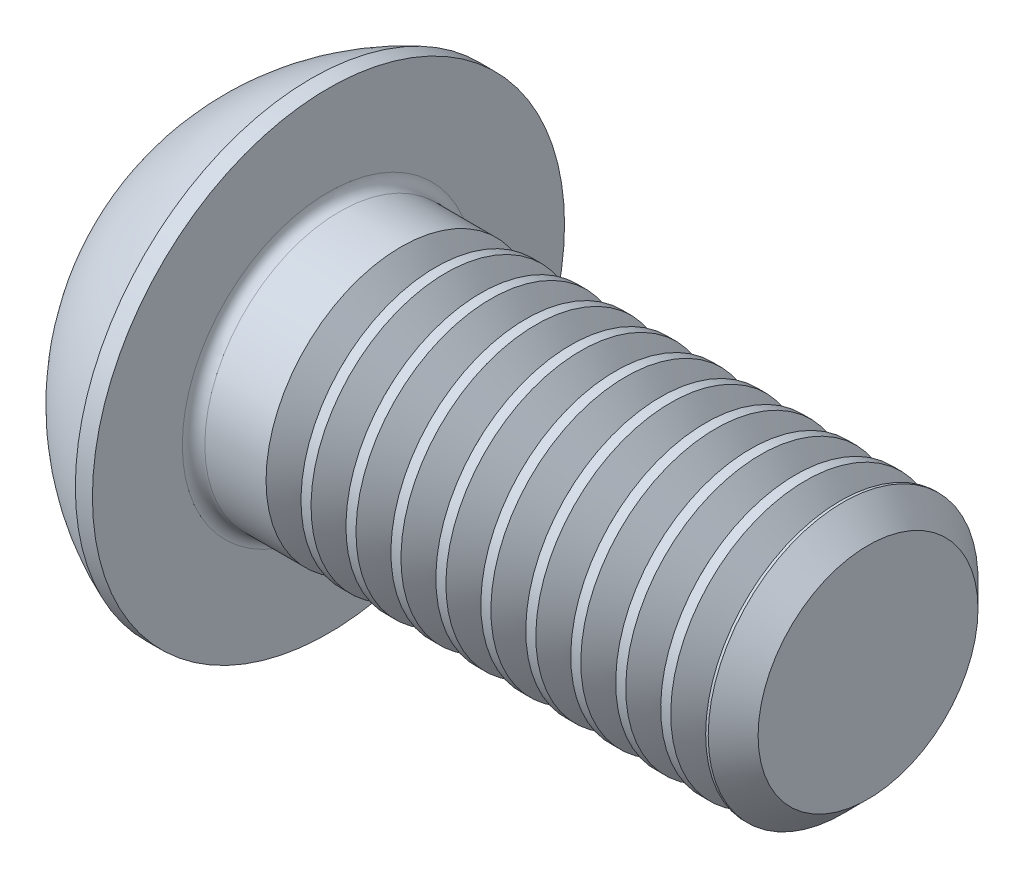
SolidWorks part; units mm, degrees
ref_plane "Plane1" through (0, 0, 0) normal (0, 0, 1) x (1, 0, 0)
ref_plane "Plane2" through (0, 0, 0) normal (0, 1, 0) x (1, 0, 0)
ref_plane "Plane3" through (0, 0, 0) normal (1, 0, 0) x (0, 0, -1)
other "Configuration Table"
sketch "BodySke" plane through (0, 0, 0) normal (0, 0, 1) x (1, 0, 0)
  line L0 (15.3, 0) -> (15.3, 2.4455)
  line L1 (14.7455, 3) -> (3.3, 3)
  line L2 (3.3, 3) -> (3.3, 5.25)
  line L3 (3.3, 5.25) -> (2.92, 5.25)
  line L4 (0, 0) -> (101.6, 0) construction
  line L5 (3.3, -5.25) -> (2.92, -5.25) construction
  line L6 (55.6768, -3) -> (3.3, -3) construction
  line L7 (15.3, 0) -> (0, 0)
  line L8 (0, 2.625) -> (0, -2.625) construction
  line L9 (0, 0) -> (0, 2.625)
  line L10 (15.3, 2.4455) -> (14.7455, 3)
  line L11 (15.3, -2.4455) -> (14.7455, -3) construction
  line L12 (4.3, 9.525) -> (4.3, -3) construction
  line L13 (3.3, 9.525) -> (3.3, -3) construction
  arc A1 (0, 2.625) -> (2.92, 5.25) centre (4.9997, 0) cw
  dimension "Diameter" = 6
  dimension "Length" = 12
  dimension "Head_dia" = 10.5
  dimension "D1" = 5.25
  dimension "Head_ht" = 3.3
  dimension "Head_side_ht" = 0.38
  dimension "Minor_dia" = 4.891
  dimension "Body_ch_ang" = 45
  dimension "Advance" = 1
  dimension "Thread_nom" = 12
revolve "BaseBody" add sketch "BodySke" angle 360 about L4
cosmetic thread "ThreadCosmetic" [suppressed] parameters "Thread_length"=10, "Thread_minor"=4.891
fillet "Fillet1" radius 0.25 1 edges at (3.3, 0, 3)
sketch "Sketch2" plane through (0, 0, 0) normal (0, 0, 1) x (1, 0, 0)
  line L0 (0, 2) -> (2.08, 2)
  line L1 (2.08, 2) -> (3.2347, 0)
  line L3 (3.2347, 0) -> (0, 0)
  line L4 (0, 0) -> (0, 2)
  line L5 (0, -2) -> (2.08, -2) construction
  line L6 (0, 0) -> (47.625, 0) construction
  dimension "D2" = 60
  dimension "PreBroach_depth" = 2.08
  dimension "PreBroach_dia" = 4
revolve "PreBroach" cut sketch "Sketch2" angle 360 about L6
sketch "Sketch3" plane through (0, 0, 0) normal (1, 0, 0) x (0, 0, -1)
  line L0 (-2, -1.1547) -> (-2, 1.1547)
  line L1 (-2, 1.1547) -> (0, 2.3094)
  line L2 (0, 2.3094) -> (2, 1.1547)
  line L3 (2, 1.1547) -> (2, -1.1547)
  line L4 (2, -1.1547) -> (0, -2.3094)
  line L5 (0, -2.3094) -> (-2, -1.1547)
  dimension "Hex_size" = 4
  dimension "D3" = 4
  dimension "D1" = 2
  dimension "D2" = 2
extrude "Hex" cut sketch "Sketch3" along normal blind 2.08
sketch "ThdSchSke" plane through (0, 0, 0) normal (0, 0, 1) x (1, 0, 0)
  line L0 (5.3, -2.4455) -> (4.9117, -3)
  line L1 (5.3, -2.4455) -> (5.6883, -3)
  line L2 (5.6883, -3) -> (5.6883, -3.75)
  line L3 (-3.175, 0) -> (5.1513, 0) construction
  line L5 (5.6883, -3.75) -> (4.9117, -3.75)
  line L6 (4.9117, -3.75) -> (4.9117, -3)
  dimension "Diameter" = 6
  dimension "Thread_minor" = 4.891
  dimension "SideAngle" = 55
  dimension "VeeAngle" = 70
  dimension "Overcut" = 7.5
  dimension "Start" = 5.3
revolve "ThreadSchematic" cut sketch "ThdSchSke" angle 360 about L3
pattern_linear "ThdSchPat" count 10 spacing 1 along (1, 0, 0) of "ThreadSchematic"
equation "\"D1@BodySke\" = \"Head_dia@BodySke\" * .5"
equation "\"Thread_minor@ThreadCosmetic\" = \"Minor_dia@BodySke\""
equation "\"D1@Sketch3\" = \"Hex_size@Sketch3\" / 2"
equation "\"D2@Sketch3\" = \"D1@Sketch3\""
equation "\"D3@Sketch3\" = \"Hex_size@Sketch3\""
equation "\"Thread_length@ThreadCosmetic\" = ((sgn( (\"Length@BodySke\" - \"Advance@BodySke\" * 2.0) - \"Thread_nom@BodySke\" )-1)*( (\"Length@BodySke\" - \"Advance@BodySke\" * 2.0) - \"Thread_nom@BodySke\" ))/-2+ \"Thread_nom@BodySke\""
equation "\"Thread_minor@ThdSchSke\" = \"Minor_dia@BodySke\""
equation "\"Diameter@ThdSchSke\" = \"Diameter@BodySke\""
equation "\"Overcut@ThdSchSke\" = \"Diameter@BodySke\" * 1.25"
equation "\"Start@ThdSchSke\" = \"Head_ht@BodySke\" + \"Length@BodySke\" - \"Thread_length@ThreadCosmetic\"  '---Non-countersunk---"
equation "\"Num_threads@ThdSchPat\" = int( \"Thread_length@ThreadCosmetic\" / \"Advance@BodySke\" + 0.999 )  + 1"
equation "\"Advance@ThdSchPat\" = \"Thread_length@ThreadCosmetic\" /  (\"Num_threads@ThdSchPat\" - 1) 'relax it"
equation "\"Num_threads@ThdSchPat\" = \"Num_threads@ThdSchPat\" - sgn( \"Num_threads@ThdSchPat\" - 1) '---chamfered tips only---"
